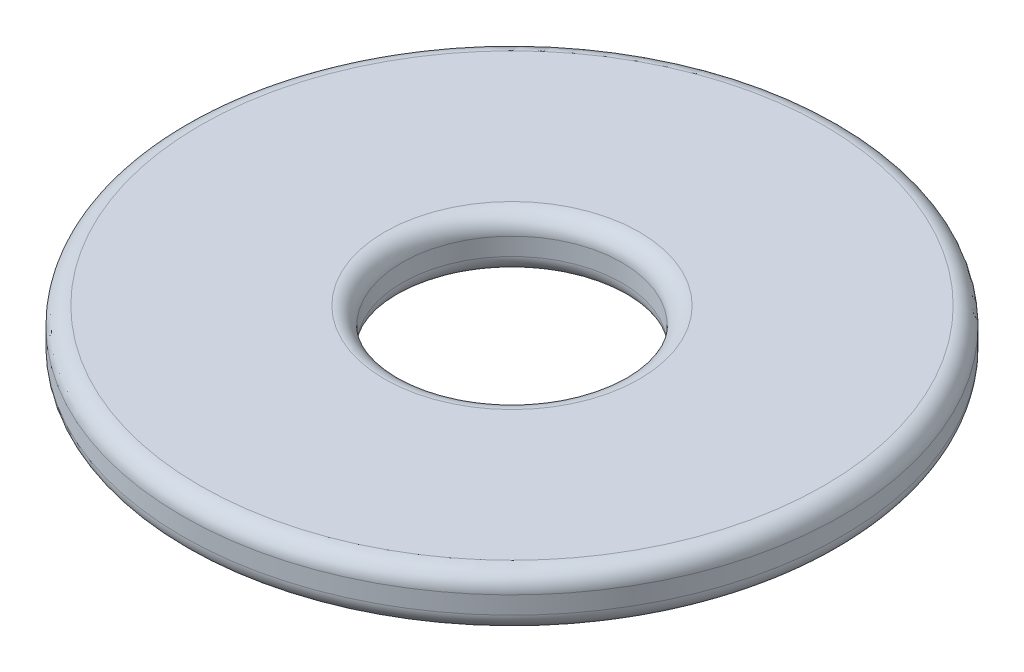
SolidWorks part; units mm, degrees
material "Cast Carbon Steel"
ref_plane "Front Plane" through (0, 0, 0) normal (0, 0, 1) x (1, 0, 0)
ref_plane "Top Plane" through (0, 0, 0) normal (0, 1, 0) x (1, 0, 0)
ref_plane "Right Plane" through (0, 0, 0) normal (1, 0, 0) x (0, 0, -1)
sketch "Sketch1" plane through (0, 0, 0) normal (0, 1, 0) x (1, 0, 0)
  circle A0 centre (0, 0) radius 7.5
  circle A1 centre (0, 0) radius 2.5
  dimension "D1" = 5
  dimension "D2" = 15
extrude "Boss-Extrude1" add sketch "Sketch1" along normal blind 1.2
fillet "Fillet1" radius 0.4 4 edges at (0, 0, 7.5) (0, 1.2, 7.5) (0, 0, 2.5) (0, 1.2, 2.5)
